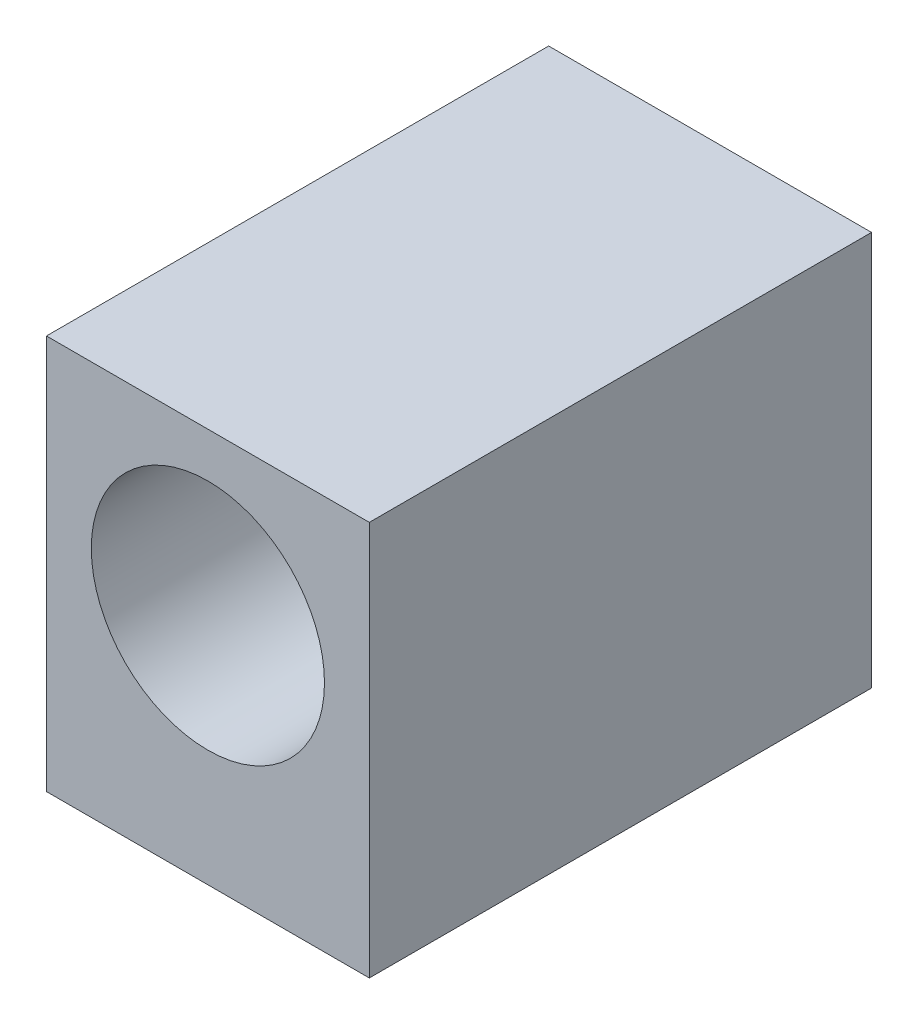
SolidWorks part; units mm, degrees
ref_plane "Front Plane" through (0, 0, 0) normal (0, 0, 1) x (1, 0, 0)
ref_plane "Top Plane" through (0, 0, 0) normal (0, 1, 0) x (1, 0, 0)
ref_plane "Right Plane" through (0, 0, 0) normal (1, 0, 0) x (0, 0, -1)
sketch "Sketch1" plane through (0, 0, 0) normal (0, 1, 0) x (1, 0, 0)
  line L1 (0, 0) -> (9, 0)
  line L2 (0, 0) -> (0, 14)
  line L3 (0, 14) -> (9, 14)
  line L4 (9, 0) -> (9, 14)
  dimension "D1" = 14
  dimension "D2" = 9
extrude "Boss-Extrude1" add sketch "Sketch1" along normal blind 11
sketch "Sketch2" plane through (0, 0, 0) normal (0, 0, 1) x (1, 0, 0)
  line L0 (0, 0) -> (9, 0) construction
  circle A0 centre (4.5, 6.5) radius 3.25
  dimension "D1" = 6.5
  dimension "D2" = 6.5
extrude "Cut-Extrude1" cut sketch "Sketch2" against normal blind 9
